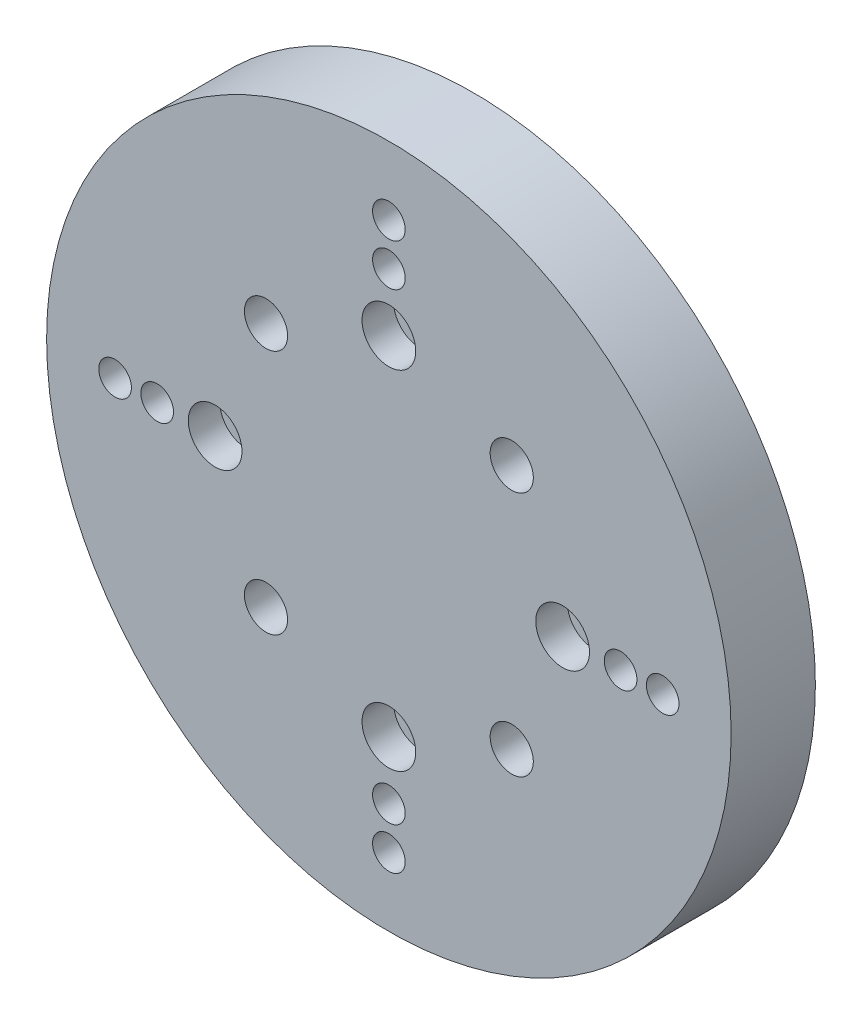
SolidWorks part; units mm, degrees
ref_plane "Front Plane" through (0, 0, 0) normal (0, 0, 1) x (1, 0, 0)
ref_plane "Top Plane" through (0, 0, 0) normal (0, 1, 0) x (1, 0, 0)
ref_plane "Right Plane" through (0, 0, 0) normal (1, 0, 0) x (0, 0, -1)
sketch "Sketch1" plane through (0, 0, 0) normal (0, 0, 1) x (1, 0, 0)
  line L0 (0, 0) -> (0, 21) construction
  circle A0 centre (0, 0) radius 55
  circle A1 centre (0, 0) radius 21 construction
  circle A2 centre (0, 21) radius 1.5
  circle A3 centre (14.8492, 14.8492) radius 1.5
  circle A4 centre (21, 0) radius 1.5
  circle A5 centre (14.8492, -14.8492) radius 1.5
  circle A6 centre (0, -21) radius 1.5
  circle A7 centre (-14.8492, -14.8492) radius 1.5
  circle A8 centre (-21, 0) radius 1.5
  circle A9 centre (-14.8492, 14.8492) radius 1.5
  dimension "D1" = 110
  dimension "D2" = 42
  dimension "D3" = 3
  dimension "D5" = 21
  dimension "D4" = 8
extrude "Boss-Extrude1" add sketch "Sketch1" along normal blind 26 contours A0
sketch "Sketch2" plane through (0, 0, 0) normal (0, 0, -1) x (-1, 0, 0)
  circle A1 centre (0, -21) radius 1.5
  circle A2 centre (0, -21) radius 1.5
  circle A3 centre (-14.8492, -14.8492) radius 1.5
  circle A4 centre (-14.8492, -14.8492) radius 1.5
  circle A5 centre (-21, 0) radius 1.5
  circle A6 centre (-21, 0) radius 1.5
  circle A7 centre (-14.8492, 14.8492) radius 1.5
  circle A8 centre (-14.8492, 14.8492) radius 1.5
  circle A9 centre (0, 21) radius 1.5
  circle A10 centre (0, 21) radius 1.5
  circle A13 centre (14.8492, 14.8492) radius 1.5
  circle A14 centre (14.8492, 14.8492) radius 1.5
  circle A15 centre (21, 0) radius 1.5
  circle A16 centre (21, 0) radius 1.5
  circle A17 centre (14.8492, -14.8492) radius 1.5
  circle A18 centre (14.8492, -14.8492) radius 1.5
  dimension "D1" = 0
  dimension "D2" = 0
  dimension "D3" = 0
  dimension "D4" = 0
  dimension "D5" = 0
  dimension "D7" = 0
  dimension "D8" = 0
  dimension "D9" = 0
extrude "Cut-Extrude1" cut sketch "Sketch2" against normal blind 3
sketch "Sketch3" plane through (0, 0, 26) normal (0, 0, 1) x (1, 0, 0)
  line L0 (0, 0) -> (0, 16.5) construction
  line L1 (0, 0) -> (-59.5603, 59.5603) construction
  line L2 (0, 0) -> (-87.189, 0) construction
  line L3 (0, 0) -> (-11.6673, 11.6673) construction
  line L4 (0, 0) -> (0, 22) construction
  circle A0 centre (0, 0) radius 26 construction
  circle A1 centre (0, 0) radius 22 construction
  circle A2 centre (0, 0) radius 16.5 construction
  circle A3 centre (0, 16.5) radius 2.55
  circle A4 centre (16.5, 0) radius 2.55
  circle A5 centre (0, -16.5) radius 2.55
  circle A6 centre (-16.5, 0) radius 2.55
  circle A7 centre (-11.6673, 11.6673) radius 2.05
  circle A8 centre (11.6673, 11.6673) radius 2.05
  circle A9 centre (11.6673, -11.6673) radius 2.05
  circle A10 centre (-11.6673, -11.6673) radius 2.05
  circle A11 centre (0, 22) radius 1.55
  circle A12 centre (0, 26) radius 1.55
  circle A13 centre (26, 0) radius 1.55
  circle A14 centre (22, 0) radius 1.55
  circle A15 centre (0, -26) radius 1.55
  circle A16 centre (0, -22) radius 1.55
  circle A17 centre (-26, 0) radius 1.55
  circle A18 centre (-22, 0) radius 1.55
  circle A19 centre (0, 0) radius 32.5
  dimension "D1" = 52
  dimension "D2" = 44
  dimension "D3" = 33
  dimension "D4" = 5.1
  dimension "D8" = 4.1
  dimension "D11" = 3.1
  dimension "D12" = 3.1
  dimension "D15" = 65
  dimension "D6" = 16.5
  dimension "D7" = 45
  dimension "D10" = 16.5
  dimension "D14" = 22
  dimension "D5" = 4
  dimension "D9" = 4
  dimension "D13" = 4
extrude "Boss-Extrude2" add sketch "Sketch3" along normal blind 8 contours A19
sketch "Sketch4" plane through (0, 0, 34) normal (0, 0, 1) x (1, 0, 0)
  circle A1 centre (-16.5, 0) radius 2.55
  circle A2 centre (-16.5, 0) radius 2.55
  circle A3 centre (0, -16.5) radius 2.55
  circle A4 centre (0, -16.5) radius 2.55
  circle A5 centre (16.5, 0) radius 2.55
  circle A6 centre (16.5, 0) radius 2.55
  circle A7 centre (0, 16.5) radius 2.55
  circle A8 centre (0, 16.5) radius 2.55
  circle A9 centre (0, 26) radius 1.55
  circle A10 centre (0, 26) radius 1.55
  circle A11 centre (0, 22) radius 1.55
  circle A12 centre (0, 22) radius 1.55
  circle A13 centre (-11.6673, -11.6673) radius 2.05
  circle A14 centre (-11.6673, -11.6673) radius 2.05
  circle A15 centre (11.6673, -11.6673) radius 2.05
  circle A16 centre (11.6673, -11.6673) radius 2.05
  circle A17 centre (11.6673, 11.6673) radius 2.05
  circle A18 centre (11.6673, 11.6673) radius 2.05
  circle A19 centre (-11.6673, 11.6673) radius 2.05
  circle A20 centre (-11.6673, 11.6673) radius 2.05
  circle A23 centre (-22, 0) radius 1.55
  circle A24 centre (-22, 0) radius 1.55
  circle A25 centre (-26, 0) radius 1.55
  circle A26 centre (-26, 0) radius 1.55
  circle A27 centre (0, -22) radius 1.55
  circle A28 centre (0, -22) radius 1.55
  circle A29 centre (0, -26) radius 1.55
  circle A30 centre (0, -26) radius 1.55
  circle A31 centre (22, 0) radius 1.55
  circle A32 centre (22, 0) radius 1.55
  circle A33 centre (26, 0) radius 1.55
  circle A34 centre (26, 0) radius 1.55
  dimension "D1" = 0
  dimension "D2" = 0
  dimension "D3" = 0
  dimension "D4" = 0
  dimension "D5" = 0
  dimension "D6" = 0
  dimension "D7" = 0
  dimension "D8" = 0
  dimension "D9" = 0
  dimension "D10" = 0
  dimension "D12" = 0
  dimension "D13" = 0
  dimension "D14" = 0
  dimension "D15" = 0
  dimension "D16" = 0
  dimension "D17" = 0
extrude "Cut-Extrude2" cut sketch "Sketch4" against normal blind 3
fillet "Fillet1" radius 2 2 edges at (55, 0, 26) (55, 0, 0)
sketch "Sketch5" plane through (0, 0, 0) normal (0, 0, -1) x (-1, 0, 0)
  line L0 (0, 53) -> (0, -53) construction
  circle A0 centre (0, 0) radius 53 construction
ref_plane "Plane1" through (0, 55, 0) normal (0, 1, 0) x (1, 0, 0)
sketch "Sketch6" plane through (0, 55, 0) normal (0, 1, 0) x (1, 0, 0)
  line L0 (0, -2) -> (0, -24) construction
  line L1 (55, -2) -> (-55, -2) construction
  line L2 (55, -24) -> (-55, -24) construction
sketch "Sketch7" plane through (0, 0, 0) normal (0, 1, 0) x (1, 0, 0)
  line L0 (0, 0) -> (0, -24) construction
  line L1 (55, -24) -> (-55, -24) construction
sketch "Sketch8" plane through (0, 0, 34) normal (0, 0, 1) x (1, 0, 0)
  line L0 (0, 0) -> (37.4767, 37.4767) construction
  line L1 (0, 0) -> (53, 0) construction
  circle A0 centre (0, 0) radius 53 construction
  dimension "D1" = 45
ref_plane "Plane2" through (0, 0, 26) normal (0, 0, 1) x (1, 0, 0)
sketch "Sketch9" plane through (0, 0, 26) normal (0, 0, 1) x (1, 0, 0)
  circle A0 centre (0, 0) radius 75
  dimension "D1" = 150
extrude "Cut-Extrude5" cut sketch "Sketch9" against normal through all
sketch "Sketch11" plane through (0, 0, 26) normal (0, 0, -1) x (-1, 0, 0)
  circle A0 centre (0, 0) radius 10
  dimension "D1" = 20
extrude "Cut-Extrude6" cut sketch "Sketch11" against normal blind 5
sketch "Sketch12" plane through (0, 0, 34) normal (0, 0, 1) x (1, 0, 0)
  circle A0 centre (0, 0) radius 16.5
